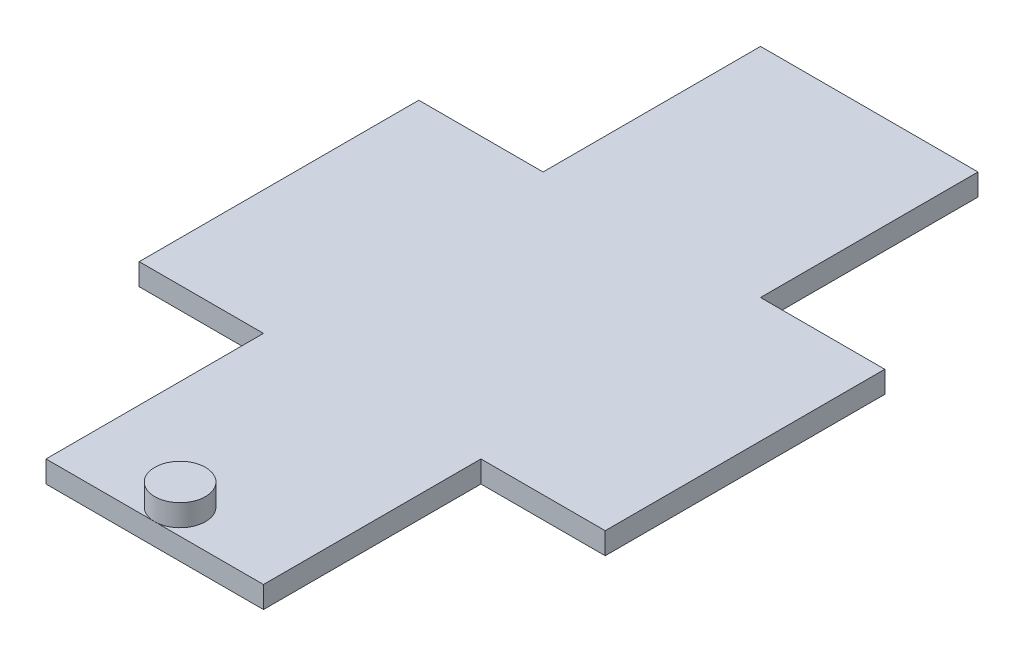
SolidWorks part; units mm, degrees
ref_plane "前视基准面" through (0, 0, 0) normal (0, 0, 1) x (1, 0, 0)
ref_plane "上视基准面" through (0, 0, 0) normal (0, 1, 0) x (1, 0, 0)
ref_plane "右视基准面" through (0, 0, 0) normal (1, 0, 0) x (0, 0, -1)
other "Configuration Table"
sketch "草图2" plane through (0, 0, 0) normal (0, 1, 0) x (1, 0, 0)
  line L4 (35, 230) -> (35, 0) construction
  line L5 (0, 230) -> (0, 160)
  line L6 (0, 160) -> (-40, 160)
  line L7 (70, 230) -> (70, 160)
  line L8 (70, 160) -> (110, 160)
  line L9 (70, 0) -> (70, 70)
  line L10 (70, 70) -> (110, 70)
  line L11 (0, 0) -> (0, 70)
  line L12 (0, 70) -> (-40, 70)
  line L24 (-40, 160) -> (-40, 70)
  line L27 (110, 70) -> (110, 160)
  line L29 (0, 230) -> (70, 230)
  line L30 (70, 0) -> (0, 0)
  dimension "D1" = 40
  dimension "D2" = 70
  dimension "D3" = 70
  dimension "D4" = 150
  dimension "D5" = 70
  dimension "D6" = 70
  dimension "D7" = 40
  dimension "D8" = 40
  dimension "D9" = 90
extrude "凸台-拉伸2" add sketch "草图2" along normal blind 7
sketch "草图3" plane through (0, 7, 0) normal (0, 1, 0) x (1, 0, 0)
  line L0 (35, 230) -> (35, 0)
  line L1 (70, 230) -> (0, 230) construction
  line L2 (0, 0) -> (70, 0) construction
  line L3 (-40, 115) -> (110, 115)
  line L4 (-40, 160) -> (-40, 70) construction
  line L5 (110, 70) -> (110, 160) construction
sketch "草图4" plane through (0, 7, 0) normal (0, 1, 0) x (1, 0, 0)
  line L0 (35, 230) -> (35, 0) construction
  circle A0 centre (35, 8.1643) radius 8.1643
extrude "凸台-拉伸3" add sketch "草图4" along normal blind 7
